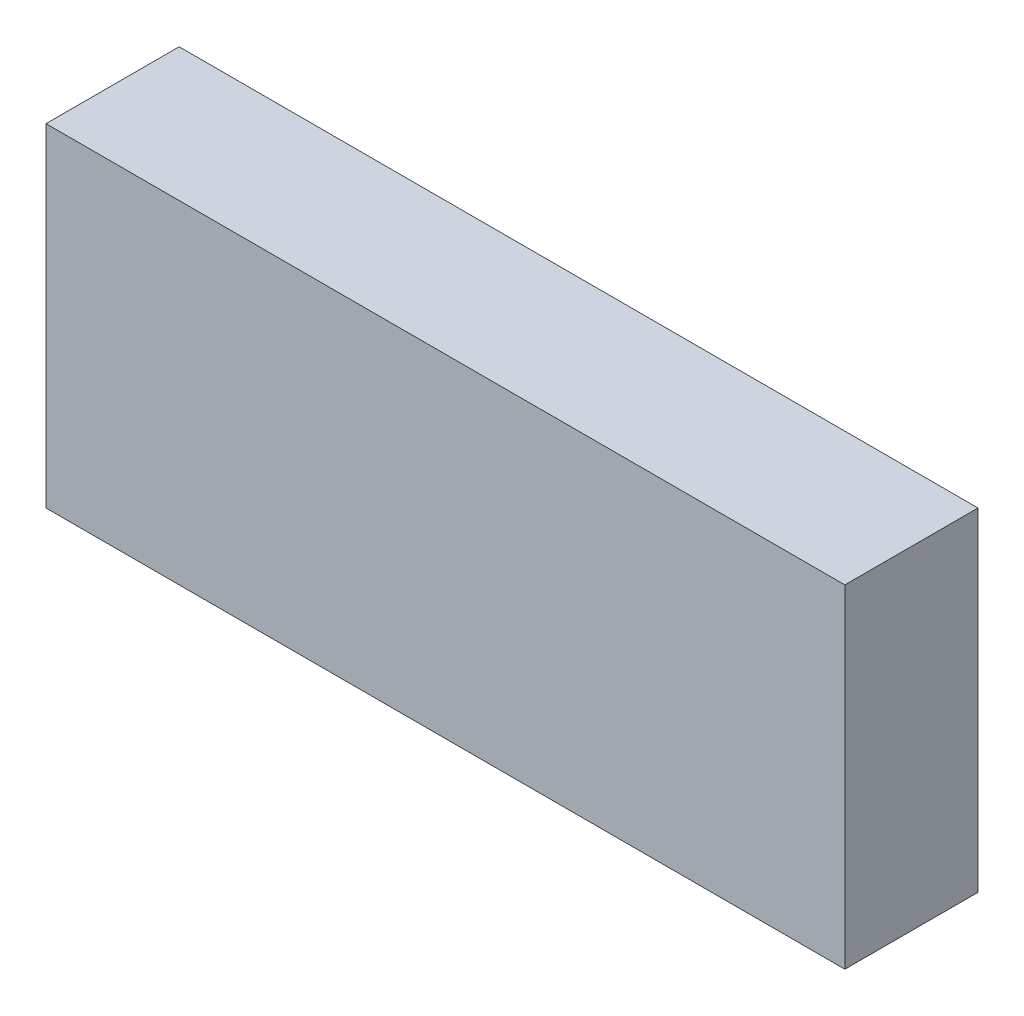
SolidWorks part; units mm, degrees
ref_plane "Alzado" through (0, 0, 0) normal (0, 0, 1) x (1, 0, 0)
ref_plane "Planta" through (0, 0, 0) normal (0, 1, 0) x (1, 0, 0)
ref_plane "Vista lateral" through (0, 0, 0) normal (1, 0, 0) x (0, 0, -1)
sketch "Croquis1" plane through (0, 0, 0) normal (0, 0, 1) x (1, 0, 0)
  line L1 (-30, -12.5) -> (30, -12.5)
  line L2 (-30, -12.5) -> (-30, 12.5)
  line L3 (-30, 12.5) -> (30, 12.5)
  line L4 (30, -12.5) -> (30, 12.5)
  line L5 (-30, -12.5) -> (30, 12.5) construction
  line L6 (-30, 12.5) -> (30, -12.5) construction
  point P0 (0, 0)
  dimension "D1" = 60
  dimension "D2" = 25
extrude "Saliente-Extruir1" add sketch "Croquis1" along normal blind 10
